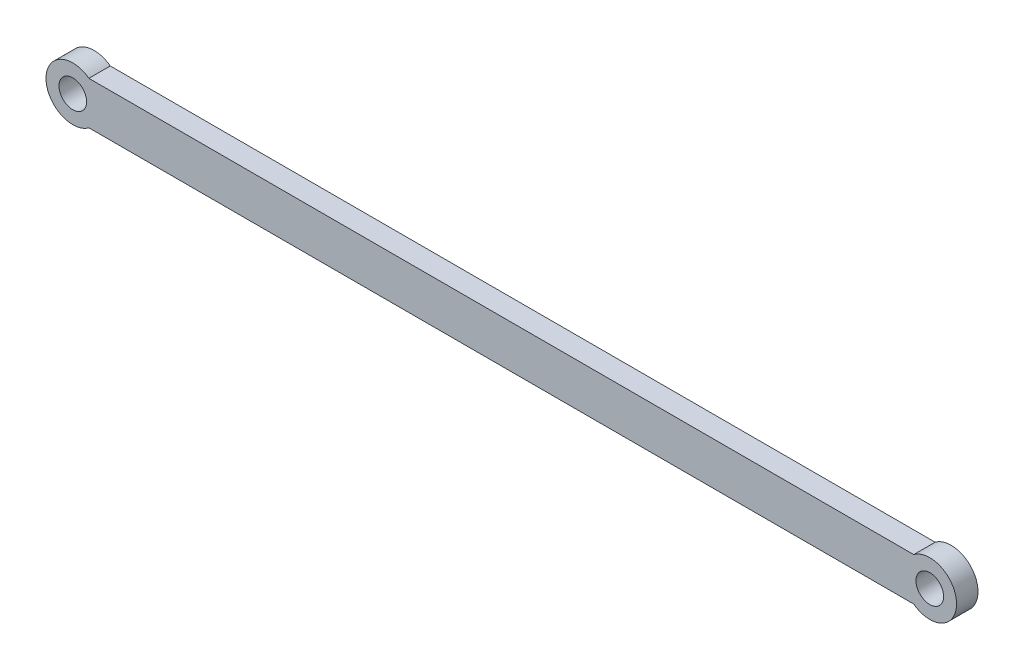
SolidWorks part; units mm, degrees
ref_plane "Front Plane" through (0, 0, 0) normal (0, 0, 1) x (1, 0, 0)
ref_plane "Top Plane" through (0, 0, 0) normal (0, 1, 0) x (1, 0, 0)
ref_plane "Right Plane" through (0, 0, 0) normal (1, 0, 0) x (0, 0, -1)
sketch "Sketch1" plane through (0, 0, 0) normal (0, 0, 1) x (1, 0, 0)
  line L1 (4.7625, 0) -> (249.2375, 0)
  line L3 (4.7625, 12.7) -> (249.2375, 12.7)
  arc A0 (4.7625, 12.7) -> (4.7625, 0) centre (0, 6.35) ccw
  arc A1 (249.2375, 0) -> (249.2375, 12.7) centre (254, 6.35) ccw
  dimension "D3" = 15.875
  dimension "D4" = 15.875
  dimension "D1" = 12.7
extrude "Boss-Extrude1" add sketch "Sketch1" along normal blind 6.35
sketch "Sketch2" plane through (0, 0, 0) normal (0, 0, -1) x (-1, 0, 0)
  circle A0 centre (-254, 6.35) radius 4.0958
  arc A1 (-249.2375, 12.7) -> (-249.2375, 0) centre (-254, 6.35) ccw construction
  circle A2 centre (0, 6.35) radius 4.0957
  arc A3 (-4.7625, 0) -> (-4.7625, 12.7) centre (0, 6.35) ccw construction
  dimension "D1" = 8.1915
  dimension "D2" = 8.1915
extrude "Cut-Extrude1" cut sketch "Sketch2" against normal up to surface (6.35 mm away) up to face at (127, 6.35, 6.35)
